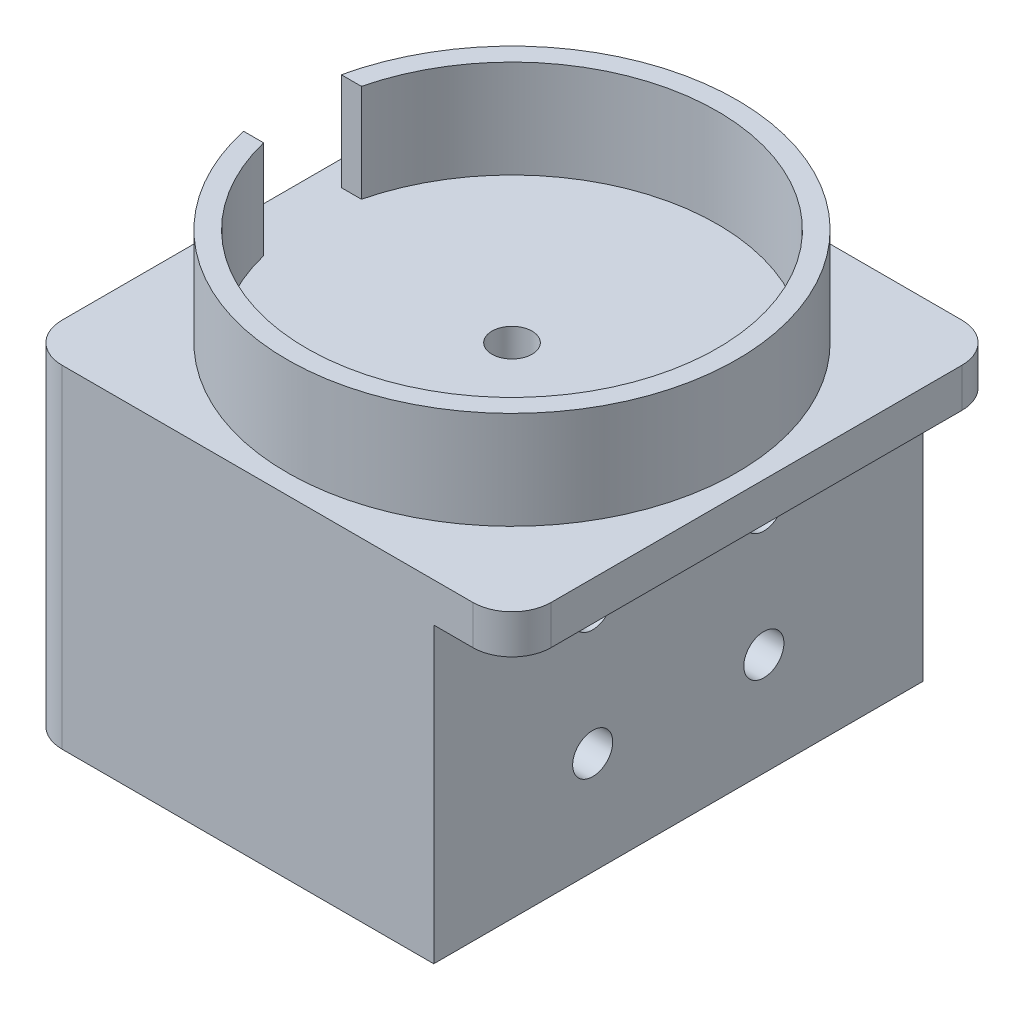
SolidWorks part; units mm, degrees
ref_plane "Front Plane" through (0, 0, 0) normal (0, 0, 1) x (1, 0, 0)
ref_plane "Top Plane" through (0, 0, 0) normal (0, 1, 0) x (1, 0, 0)
ref_plane "Right Plane" through (0, 0, 0) normal (1, 0, 0) x (0, 0, -1)
sketch "Sketch1" plane through (0, 0, 0) normal (0, 1, 0) x (1, 0, 0)
  line L0 (42, 50) -> (42, 0)
  line L1 (4, 0) -> (50, 0)
  line L2 (0, 4) -> (0, 46)
  line L3 (4, 50) -> (50, 50)
  line L4 (50, 0) -> (50, 50)
  arc A0 (4, 0) -> (0, 4) centre (4, 4) cw
  arc A1 (0, 46) -> (4, 50) centre (4, 46) cw
  point P7 (0, 0)
  point P10 (0, 50)
  dimension "D3" = 4
  dimension "D1" = 50
  dimension "D2" = 50
  dimension "D4" = 8
extrude "Boss-Extrude1" add sketch "Sketch1" along normal blind 30 contours A1 L2 A0 L1 L0 L3
sketch "Sketch3" plane through (0, 0, 0) normal (0, 0, 1) x (1, 0, 0)
  line L0 (42, 30) -> (42, 0) construction
  line L1 (34, 4) -> (0, 4)
  line L2 (34, 4) -> (34, 30)
  line L3 (34, 30) -> (0, 30)
  line L4 (0, 4) -> (0, 30)
  line L5 (0, 30) -> (0, 0) construction
  line L6 (4, 0) -> (42, 0) construction
  line L7 (4, 30) -> (42, 30) construction
  dimension "D1" = 8
  dimension "D2" = 0
  dimension "D3" = 4
  dimension "D4" = 0
extrude "Cut-Extrude1" cut sketch "Sketch3" against normal blind 35 from offset 7.5 offset against normal yes
sketch "Sketch6" plane through (0, 4, 0) normal (0, 1, 0) x (1, 0, 0)
  line L0 (0, 25) -> (34, 25)
  line L1 (0, 42.5) -> (0, 7.5) construction
  line L2 (34, 42.5) -> (34, 7.5) construction
  line L3 (25, 42.5) -> (25, 7.5)
  line L4 (0, 42.5) -> (34, 42.5) construction
  line L5 (0, 7.5) -> (34, 7.5) construction
  circle A0 centre (25, 25) radius 2
  circle A1 centre (15, 25) radius 2
  circle A2 centre (25, 15) radius 2
  circle A3 centre (25, 35) radius 2
  dimension "D2" = 4
  dimension "D3" = 10
  dimension "D1" = 25
  dimension "D4" = 10
  dimension "D5" = 10
hole_wizard "Ø4.0mm Dowel Hole2" positions "3DSketch2" profile "Sketch7" hole size "Ø4.0" standard "ANSI Metric" end condition through all
sketch3d "3DSketch2"
  point P0 (25, 4, -35)
  point P3 (25, 4, -25)
  point P6 (25, 4, -15)
  point P9 (15, 4, -25)
sketch "Sketch7" plane through (25, 4, -35) normal (1, 0, 0) x (0, 0, 1)
  line L0 (0, 0) -> (0, 4)
  line L1 (0, 4) -> (2.05, 4)
  line L2 (2.05, 4) -> (2.05, 0)
  line L5 (2.05, 0) -> (0, 0)
  line L11 (0, -6.35) -> (0, 107.95) construction
  dimension "Thru Hole Dia." = 4.1
  dimension "Thru Hole Depth" = 4
sketch "Sketch2" plane through (42, 0, 0) normal (1, 0, 0) x (0, 0, -1)
  line L0 (0, 1.5) -> (50, 1.5)
  line L1 (50, 30) -> (50, 0) construction
  line L2 (50, 1.5) -> (50, 7.5)
  line L3 (50, 7.5) -> (0, 7.5)
  line L4 (0, 30) -> (0, 0) construction
  line L5 (0, 7.5) -> (0, 1.5)
  line L6 (50, 0) -> (0, 0) construction
  line L8 (0, 13.5) -> (50, 13.5)
  line L9 (0, 13.5) -> (0, 19.5)
  line L10 (0, 19.5) -> (50, 19.5)
  line L11 (50, 13.5) -> (50, 19.5)
  line L12 (25, 30) -> (25, 0) construction
  line L13 (50, 30) -> (0, 30) construction
  circle A0 centre (16.25, 23.5) radius 2
  circle A1 centre (33.75, 23.5) radius 2
  circle A2 centre (33.75, 10.5) radius 2
  circle A3 centre (16.25, 10.5) radius 2
  dimension "D5" = 4
  dimension "D1" = 6
  dimension "D2" = 1.5
  dimension "D3" = 6
  dimension "D4" = 12
  dimension "D6" = 3
  dimension "D7" = 3
  dimension "D8" = 4
  dimension "D9" = 4
  dimension "D10" = 8.75
  dimension "D11" = 8.75
  dimension "D12" = 8.75
  dimension "D13" = 8.75
hole_wizard "Ø4.0mm Dowel Hole1" positions "3DSketch1" profile "Sketch4" hole size "Ø4.0" standard "ANSI Metric" end condition through all
sketch3d "3DSketch1"
  point P0 (42, 23.5, -16.25)
  point P3 (42, 23.5, -33.75)
  point P6 (42, 10.5, -33.75)
  point P9 (42, 10.5, -16.25)
sketch "Sketch4" plane through (42, 23.5, -16.25) normal (0, 1, 0) x (0, 0, -1)
  line L0 (0, 0) -> (0, 42)
  line L1 (0, 42) -> (2.05, 42)
  line L2 (2.05, 42) -> (2.05, 0)
  line L5 (2.05, 0) -> (0, 0)
  line L11 (0, -6.35) -> (0, 107.95) construction
  dimension "Thru Hole Dia." = 4.1
  dimension "Thru Hole Depth" = 42
sketch "Sketch5" plane through (0, 30, 0) normal (0, 1, 0) x (1, 0, 0)
  line L1 (4, 0) -> (46, 0)
  line L2 (0, 4) -> (0, 46)
  line L3 (4, 50) -> (46, 50)
  line L4 (50, 4) -> (50, 46)
  arc A0 (46, 50) -> (50, 46) centre (46, 46) cw
  arc A1 (46, 0) -> (50, 4) centre (46, 4) ccw
  arc A2 (4, 0) -> (0, 4) centre (4, 4) cw
  arc A3 (0, 46) -> (4, 50) centre (4, 46) cw
  point P7 (50, 50)
  point P12 (0, 0)
  point P15 (0, 50)
  dimension "D3" = 4
  dimension "D1" = 50
  dimension "D2" = 50
extrude "Boss-Extrude2" add sketch "Sketch5" along normal blind 4
sketch "Sketch8" plane through (0, 34, 0) normal (0, 1, 0) x (1, 0, 0)
  line L0 (46, 50) -> (4, 50) construction
  line L1 (0, 46) -> (0, 4) construction
  line L2 (2.5501, 30) -> (4.6039, 30)
  line L3 (4.6039, 20) -> (2.5501, 20)
  circle A0 centre (25, 25) radius 21
  circle A1 centre (25, 25) radius 23
  dimension "D1" = 42
  dimension "D4" = 2
  dimension "D2" = 25
  dimension "D3" = 25
  dimension "D5" = 10
  dimension "D6" = 5
extrude "Boss-Extrude3" add sketch "Sketch8" along normal blind 10 contours L3 A1 L2 A0
hole_wizard "Ø4.0mm Dowel Hole3" positions "3DSketch3" profile "Sketch9" hole size "Ø4.0" standard "ANSI Metric" end condition up to next
sketch3d "3DSketch3"
  line L0 (25, 44, -25) -> (25, 34, -25) construction
  point P0 (25, 44, -25)
sketch "Sketch9" plane through (25, 44, -25) normal (1, 0, 0) x (0, 0, 1)
  line L0 (0, 0) -> (0, 14)
  line L1 (0, 14) -> (2.05, 14)
  line L2 (2.05, 14) -> (2.05, 0)
  line L5 (2.05, 0) -> (0, 0)
  line L11 (0, -6.35) -> (0, 107.95) construction
  dimension "Thru Hole Dia." = 4.1
  dimension "Thru Hole Depth" = 14
